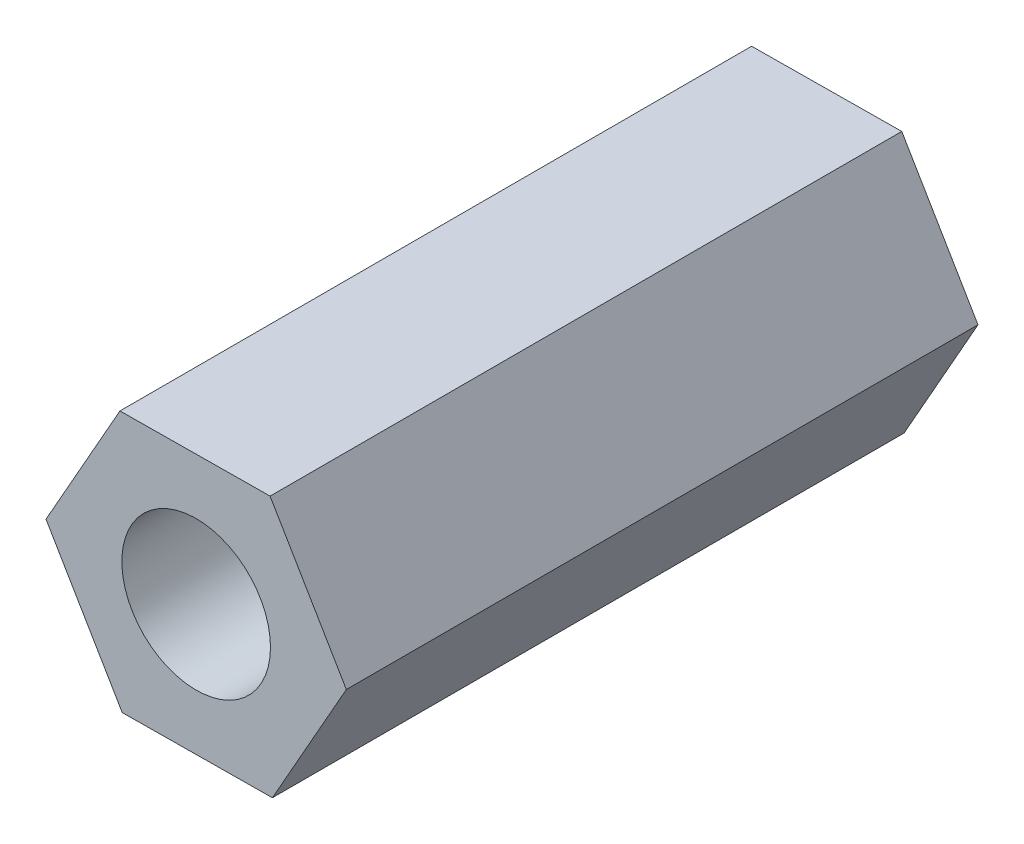
SolidWorks part; units mm, degrees
ref_plane "前视基准面" through (0, 0, 0) normal (0, 0, 1) x (1, 0, 0)
ref_plane "上视基准面" through (0, 0, 0) normal (0, 1, 0) x (1, 0, 0)
ref_plane "右视基准面" through (0, 0, 0) normal (1, 0, 0) x (0, 0, -1)
sketch "草图1" plane through (0, 0, 0) normal (0, 0, 1) x (1, 0, 0)
  line L1 (2.0515, -3.4821) -> (4.0413, 0.0356)
  line L2 (4.0413, 0.0356) -> (1.9898, 3.5177)
  line L3 (1.9898, 3.5177) -> (-2.0515, 3.4821)
  line L4 (-2.0515, 3.4821) -> (-4.0413, -0.0356)
  line L5 (-4.0413, -0.0356) -> (-1.9898, -3.5177)
  line L6 (-1.9898, -3.5177) -> (2.0515, -3.4821)
  circle A0 centre (0, 0) radius 3.5 construction
  circle A1 centre (0, 0) radius 2
extrude "凸台-拉伸1" add sketch "草图1" along normal blind 17
